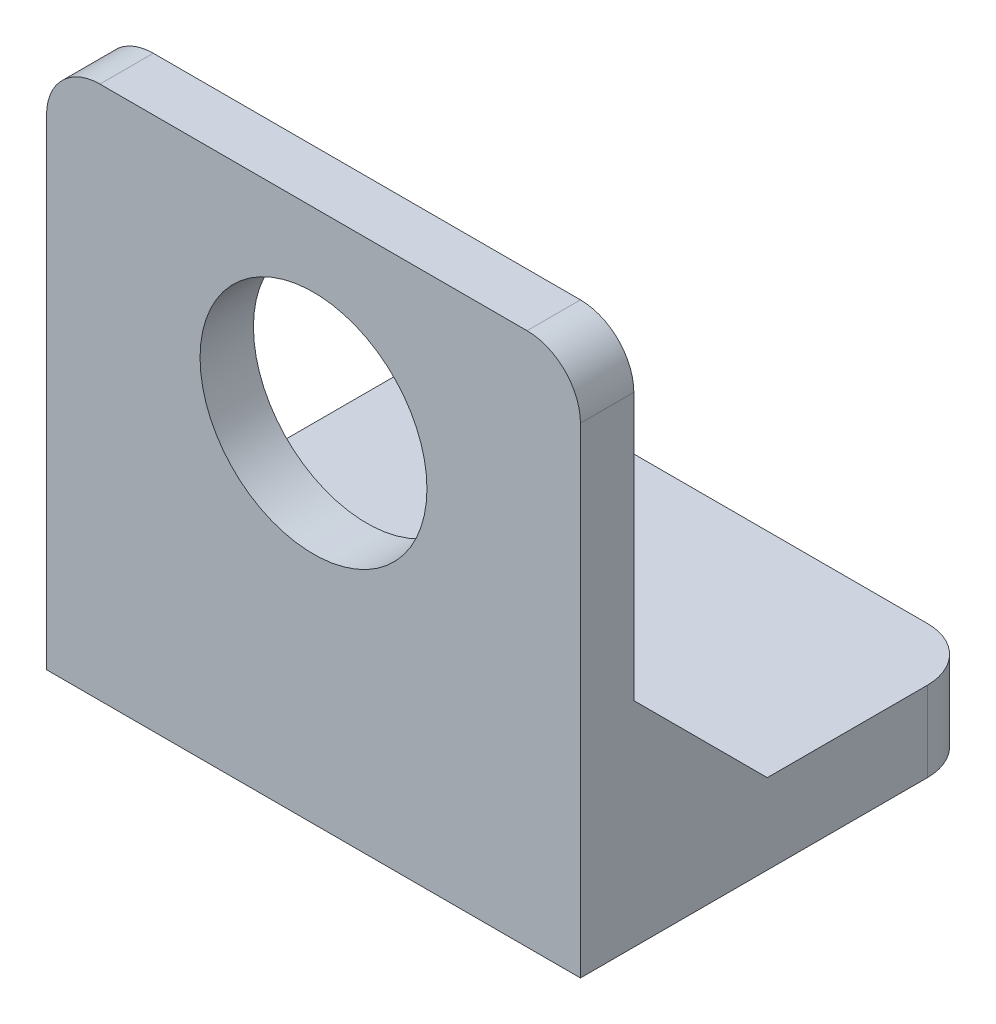
SolidWorks part; units mm, degrees
ref_plane "Přední rovina" through (0, 0, 0) normal (0, 0, 1) x (1, 0, 0)
ref_plane "Horní rovina" through (0, 0, 0) normal (0, 1, 0) x (1, 0, 0)
ref_plane "Pravá rovina" through (0, 0, 0) normal (1, 0, 0) x (0, 0, -1)
sketch "Skica1" plane through (0, 0, 0) normal (0, 0, 1) x (1, 0, 0)
  line L1 (-10, 7) -> (10, 7)
  line L2 (-10, 7) -> (-10, -13)
  line L3 (-10, -13) -> (10, -13)
  line L4 (10, 7) -> (10, -13)
  line L5 (4.8, 2.7713) -> (0, 5.5426) construction
  line L6 (0, 5.5426) -> (-4.8, 2.7713) construction
  line L7 (-4.8, 2.7713) -> (-4.8, -2.7713) construction
  line L8 (-4.8, -2.7713) -> (0, -5.5426) construction
  line L9 (0, -5.5426) -> (4.8, -2.7713) construction
  line L10 (4.8, -2.7713) -> (4.8, 2.7713) construction
  circle A0 centre (0, 0) radius 4.25
  circle A1 centre (0, 0) radius 4.8 construction
  circle A2 centre (0, 0) radius 5.5426 construction
  point P8 (0, 7)
  dimension "D1" = 8.5
  dimension "D2" = 20
  dimension "D3" = 7
  dimension "D4" = 20
  dimension "D5" = 9.6
extrude "Přidat vysunutím1" add sketch "Skica1" against normal blind 2
sketch "Skica2" plane through (0, 0, -2) normal (0, 0, -1) x (-1, 0, 0)
  line L0 (10, 7) -> (10, -13) construction
  line L1 (-10, -13) -> (10, -13)
  line L2 (-10, -13) -> (-10, -10)
  line L3 (-10, -10) -> (10, -10)
  line L4 (10, -13) -> (10, -10)
  dimension "D1" = 3
extrude "Přidat vysunutím2" add sketch "Skica2" along normal blind 15 from surface at -2 starting at face at (4.25, 0, 0)
sketch "Skica3" plane through (-10, 0, 0) normal (-1, 0, 0) x (0, 0, 1)
  line L0 (-2, -10) -> (-7, -10)
  line L1 (-15, -10) -> (-2, -10) construction
  line L2 (-7, -10) -> (-2, -5)
  line L3 (-2, 7) -> (-2, -10) construction
  line L4 (-2, -5) -> (-2, -10)
  dimension "D1" = 5
  dimension "D2" = 5
extrude "Přidat vysunutím3" add sketch "Skica3" against normal blind 2
mirror "Zrcadlit1" about plane through (0, 0, 0) normal (1, 0, 0) of "Přidat vysunutím3"
fillet "Zaoblit1" radius 2 2 edges at (-10, 7, -1) (10, 7, -1)
fillet "Zaoblit2" radius 2 2 edges at (-10, -11.5, -15) (10, -11.5, -15)
